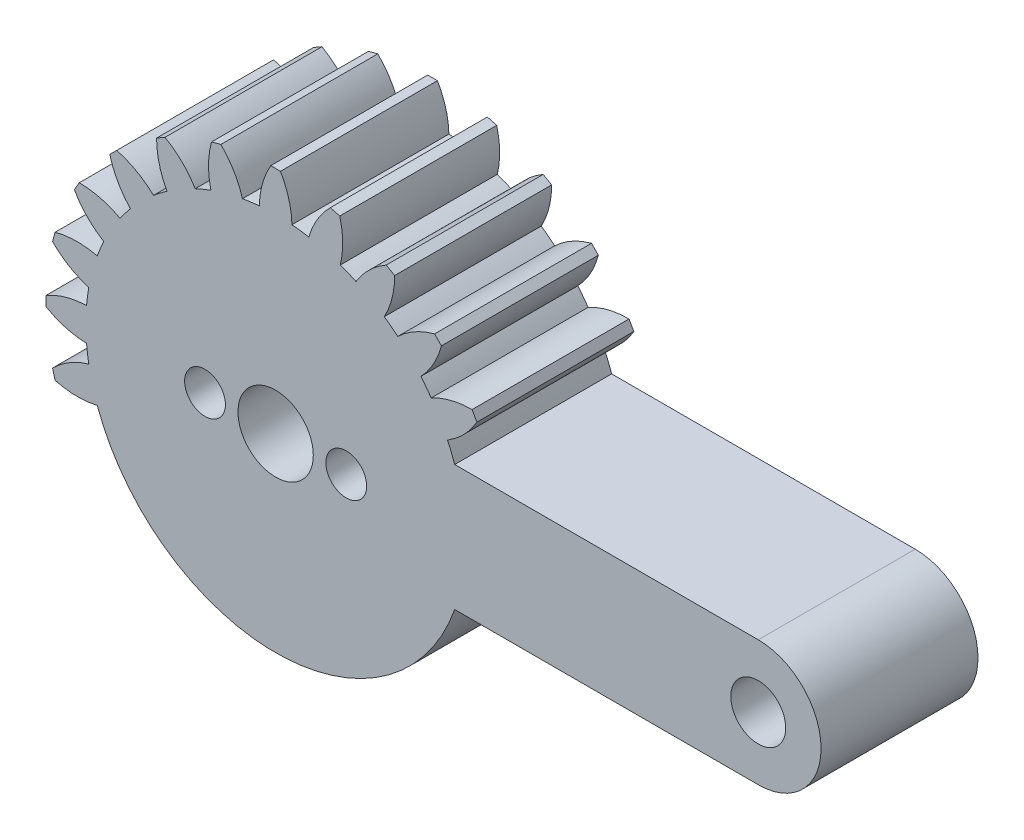
SolidWorks part; units mm, degrees
ref_plane "Front Plane" through (0, 0, 0) normal (0, 0, 1) x (1, 0, 0)
ref_plane "Top Plane" through (0, 0, 0) normal (0, 1, 0) x (1, 0, 0)
ref_plane "Right Plane" through (0, 0, 0) normal (1, 0, 0) x (0, 0, -1)
sketch "Sketch1" plane through (0, 0, 0) normal (0, 0, 1) x (1, 0, 0)
  line L0 (0, 0) -> (30.75, 0) construction
  line L1 (0, 14.63) -> (0, -14.63) construction
  line L2 (-0.31, 14.63) -> (0.31, 14.63)
  line L3 (3.4871, 14.2117) -> (4.086, 14.0513)
  line L4 (7.0465, 12.825) -> (7.5835, 12.515)
  line L5 (10.1258, 10.5642) -> (10.5642, 10.1258)
  line L6 (12.515, 7.5835) -> (12.825, 7.0465)
  line L7 (14.0513, 4.086) -> (14.2117, 3.4871)
  line L8 (14.63, 0.31) -> (14.63, -0.31)
  line L9 (14.2117, -3.4871) -> (14.0513, -4.086)
  line L10 (12.825, -7.0465) -> (12.515, -7.5835)
  line L11 (10.5642, -10.1258) -> (10.1258, -10.5642)
  line L12 (7.5835, -12.515) -> (7.0465, -12.825)
  line L13 (4.086, -14.0513) -> (3.4871, -14.2117)
  line L14 (0.31, -14.63) -> (-0.31, -14.63)
  line L15 (-3.4871, -14.2117) -> (-4.086, -14.0513)
  line L16 (-7.0465, -12.825) -> (-7.5835, -12.515)
  line L17 (-10.1258, -10.5642) -> (-10.5642, -10.1258)
  line L18 (-12.515, -7.5835) -> (-12.825, -7.0465)
  line L19 (-14.0513, -4.086) -> (-14.2117, -3.4871)
  line L20 (-14.63, -0.31) -> (-14.63, 0.31)
  line L21 (-14.2117, 3.4871) -> (-14.0513, 4.086)
  line L22 (-12.825, 7.0465) -> (-12.515, 7.5835)
  line L23 (-10.5642, 10.1258) -> (-10.1258, 10.5642)
  line L24 (-7.5835, 12.515) -> (-7.0465, 12.825)
  line L25 (-4.086, 14.0513) -> (-3.4871, 14.2117)
  line L26 (30.75, -4) -> (30.75, 4) construction
  line L27 (30.75, -4) -> (11.4091, -4)
  line L28 (30.75, 4) -> (11.4091, 4)
  circle A0 centre (0, 0) radius 1.75
  circle A1 centre (0, 0) radius 12.09
  circle A2 centre (30.75, 0) radius 1.75
  arc A3 (-1.04, 12.0452) -> (-0.31, 14.63) centre (4.3585, 11.9161) cw
  arc A4 (1.04, 12.0452) -> (0.31, 14.63) centre (-4.3585, 11.9161) ccw
  arc A5 (2.113, 11.9039) -> (3.4871, 14.2117) centre (7.294, 10.382) cw
  arc A6 (4.1221, 11.3656) -> (4.086, 14.0513) centre (-1.1258, 12.6381) ccw
  arc A7 (5.1219, 10.9514) -> (7.0465, 12.825) centre (9.7326, 8.1404) cw
  arc A8 (6.9233, 9.9114) -> (7.5835, 12.515) centre (2.1835, 12.4988) ccw
  arc A9 (7.7818, 9.2526) -> (10.1258, 10.5642) centre (11.5078, 5.344) cw
  arc A10 (9.2526, 7.7818) -> (10.5642, 10.1258) centre (5.344, 11.5078) ccw
  arc A11 (9.9114, 6.9233) -> (12.515, 7.5835) centre (12.4988, 2.1835) cw
  arc A12 (10.9514, 5.1219) -> (12.825, 7.0465) centre (8.1404, 9.7326) ccw
  arc A13 (11.3656, 4.1221) -> (14.0513, 4.086) centre (12.6381, -1.1258) cw
  arc A14 (11.9039, 2.113) -> (14.2117, 3.4871) centre (10.382, 7.294) ccw
  arc A15 (12.0452, 1.04) -> (14.63, 0.31) centre (11.9161, -4.3585) cw
  arc A16 (12.0452, -1.04) -> (14.63, -0.31) centre (11.9161, 4.3585) ccw
  arc A17 (11.9039, -2.113) -> (14.2117, -3.4871) centre (10.382, -7.294) cw
  arc A18 (11.3656, -4.1221) -> (14.0513, -4.086) centre (12.6381, 1.1258) ccw
  arc A19 (10.9514, -5.1219) -> (12.825, -7.0465) centre (8.1404, -9.7326) cw
  arc A20 (9.9114, -6.9233) -> (12.515, -7.5835) centre (12.4988, -2.1835) ccw
  arc A21 (9.2526, -7.7818) -> (10.5642, -10.1258) centre (5.344, -11.5078) cw
  arc A22 (7.7818, -9.2526) -> (10.1258, -10.5642) centre (11.5078, -5.344) ccw
  arc A23 (6.9233, -9.9114) -> (7.5835, -12.515) centre (2.1835, -12.4988) cw
  arc A24 (5.1219, -10.9514) -> (7.0465, -12.825) centre (9.7326, -8.1404) ccw
  arc A25 (4.1221, -11.3656) -> (4.086, -14.0513) centre (-1.1258, -12.6381) cw
  arc A26 (2.113, -11.9039) -> (3.4871, -14.2117) centre (7.294, -10.382) ccw
  arc A27 (1.04, -12.0452) -> (0.31, -14.63) centre (-4.3585, -11.9161) cw
  arc A28 (-1.04, -12.0452) -> (-0.31, -14.63) centre (4.3585, -11.9161) ccw
  arc A29 (-2.113, -11.9039) -> (-3.4871, -14.2117) centre (-7.294, -10.382) cw
  arc A30 (-4.1221, -11.3656) -> (-4.086, -14.0513) centre (1.1258, -12.6381) ccw
  arc A31 (-5.1219, -10.9514) -> (-7.0465, -12.825) centre (-9.7326, -8.1404) cw
  arc A32 (-6.9233, -9.9114) -> (-7.5835, -12.515) centre (-2.1835, -12.4988) ccw
  arc A33 (-7.7818, -9.2526) -> (-10.1258, -10.5642) centre (-11.5078, -5.344) cw
  arc A34 (-9.2526, -7.7818) -> (-10.5642, -10.1258) centre (-5.344, -11.5078) ccw
  arc A35 (-9.9114, -6.9233) -> (-12.515, -7.5835) centre (-12.4988, -2.1835) cw
  arc A36 (-10.9514, -5.1219) -> (-12.825, -7.0465) centre (-8.1404, -9.7326) ccw
  arc A37 (-11.3656, -4.1221) -> (-14.0513, -4.086) centre (-12.6381, 1.1258) cw
  arc A38 (-11.9039, -2.113) -> (-14.2117, -3.4871) centre (-10.382, -7.294) ccw
  arc A39 (-12.0452, -1.04) -> (-14.63, -0.31) centre (-11.9161, 4.3585) cw
  arc A40 (-12.0452, 1.04) -> (-14.63, 0.31) centre (-11.9161, -4.3585) ccw
  arc A41 (-11.9039, 2.113) -> (-14.2117, 3.4871) centre (-10.382, 7.294) cw
  arc A42 (-11.3656, 4.1221) -> (-14.0513, 4.086) centre (-12.6381, -1.1258) ccw
  arc A43 (-10.9514, 5.1219) -> (-12.825, 7.0465) centre (-8.1404, 9.7326) cw
  arc A44 (-9.9114, 6.9233) -> (-12.515, 7.5835) centre (-12.4988, 2.1835) ccw
  arc A45 (-9.2526, 7.7818) -> (-10.5642, 10.1258) centre (-5.344, 11.5078) cw
  arc A46 (-7.7818, 9.2526) -> (-10.1258, 10.5642) centre (-11.5078, 5.344) ccw
  arc A47 (-6.9233, 9.9114) -> (-7.5835, 12.515) centre (-2.1835, 12.4988) cw
  arc A48 (-5.1219, 10.9514) -> (-7.0465, 12.825) centre (-9.7326, 8.1404) ccw
  arc A49 (-4.1221, 11.3656) -> (-4.086, 14.0513) centre (1.1258, 12.6381) cw
  arc A50 (-2.113, 11.9039) -> (-3.4871, 14.2117) centre (-7.294, 10.382) ccw
  arc A51 (30.75, -4) -> (30.75, 4) centre (30.75, 0) ccw
  point P9 (0, 0)
  point P157 (30.75, 0)
  dimension "D2" = 3.5
  dimension "D3" = 24.18
  dimension "D5" = 5.4
  dimension "D9" = 8
  dimension "D1" = 30.75
  dimension "D4" = 29.26
  dimension "D6" = 0.31
  dimension "D7" = 1.04
  dimension "D8" = 24
extrude "Boss-Extrude1" add sketch "Sketch1" along normal blind 10 contours L27 A51 L28 L7 A14 A1 A15 L8 A16 A17 L9 A2 | A1 | A1 A12 L6 A11 | A1 A10 L5 A9 | A1 A8 L4 A7 | A1 A6 L3 A5 | A1 A4 L2 A3 | A1 A50 L25 A49 | A1 A48 L24 A47 | A1 A46 L23 A45 | A1 A44 L22 A43 | A1 A42 L21 A41 | A1 A40 L20 A39 | A1 A14 L7 L28 | A1 A16 L8 A15 | A17 A1 L27 L9 | A1 A38 L19 A37
sketch "Sketch2" plane through (0, 0, 10) normal (0, 0, 1) x (1, 0, 0)
  line L0 (-4.5, 0) -> (4.5, 0) construction
  circle A0 centre (-4.5, 0) radius 1.3
  circle A1 centre (0, 0) radius 2.4
  circle A2 centre (4.5, 0) radius 1.3
  point P5 (0, 0)
  dimension "D2" = 2.6
  dimension "D3" = 2.6
  dimension "D4" = 4.8
  dimension "D1" = 9
extrude "Cut-Extrude1" cut sketch "Sketch2" against normal through all
